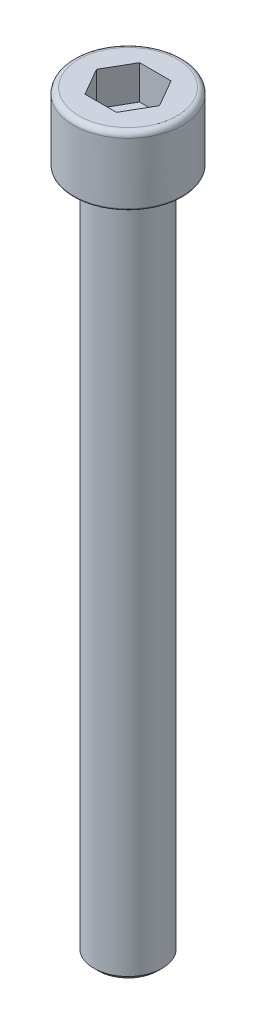
SolidWorks part; units mm, degrees
material "Plain Carbon Steel"
ref_plane "Front Plane" through (0, 0, 0) normal (0, 0, 1) x (1, 0, 0)
ref_plane "Top Plane" through (0, 0, 0) normal (0, 1, 0) x (1, 0, 0)
ref_plane "Right Plane" through (0, 0, 0) normal (1, 0, 0) x (0, 0, -1)
sketch "Sketch1" plane through (0, 0, 0) normal (0, 0, 1) x (1, 0, 0)
  line L0 (0, 0) -> (8, 0)
  line L1 (8, 0) -> (8, -10)
  line L2 (8, -10) -> (5, -10)
  line L3 (5, -10) -> (5, -110)
  line L4 (5, -110) -> (0, -110)
  line L5 (0, -110) -> (0, 0)
  line L6 (0, -115) -> (0, 5) construction
  dimension "D1" = 5
  dimension "D2" = 5
  dimension "H" = 10
  dimension "L" = 100
  dimension "D" = 10
  dimension "A" = 16
revolve "Revolve1" add sketch "Sketch1" angle 360 about L6
sketch "Sketch2" plane through (0, 0, 0) normal (0, 1, 0) x (1, 0, 0)
  line L7 (4.6188, 0) -> (2.3094, 4)
  line L8 (2.3094, 4) -> (-2.3094, 4)
  line L9 (-2.3094, 4) -> (-4.6188, 0)
  line L10 (-4.6188, 0) -> (-2.3094, -4)
  line L11 (-2.3094, -4) -> (2.3094, -4)
  line L12 (2.3094, -4) -> (4.6188, 0)
  circle A0 centre (0, 0) radius 4 construction
  dimension "D1" = 8
extrude "Cut-Extrude1" cut sketch "Sketch2" against normal blind 5
fillet "Fillet3" radius 0.8 1 edges at (0, 0, -8)
chamfer "Chamfer1" distance 0.625 angle 45 1 edges at (0, -110, -5)
cosmetic thread "Cosmetic Thread1" parameters "B"=32, "D2"=8.344
ref_plane "ThreadStop" through (0, -13.75, 0) normal (0, -1, 0) x (-1, 0, 0)
fillet "Fillet4" radius 0.25 2 edges at (0, -10, -5) (0, -10, -8)
